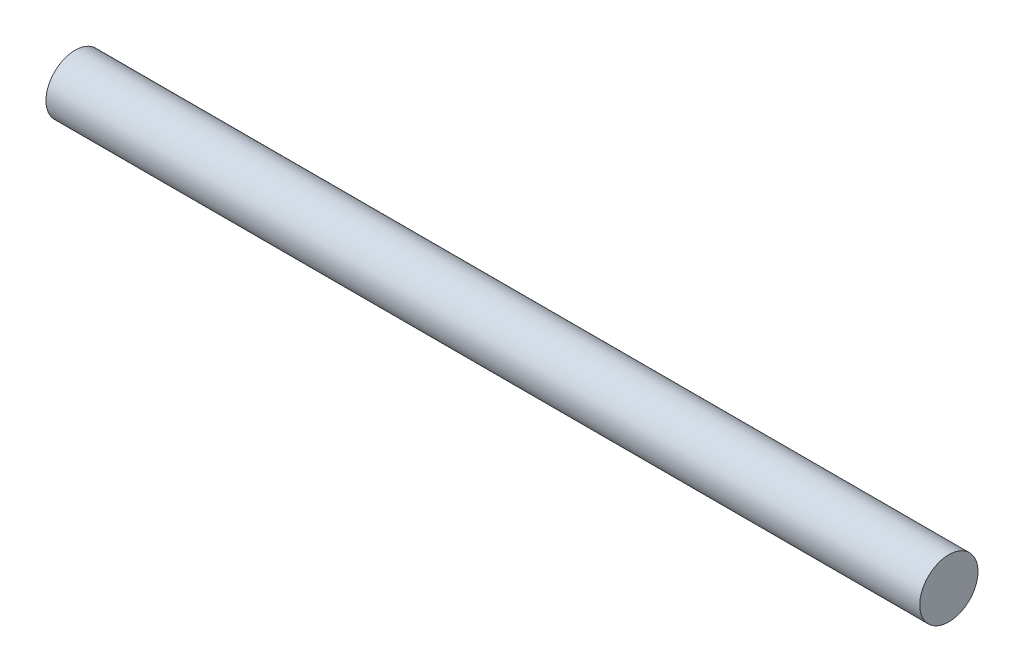
SolidWorks part; units mm, degrees
material "6061 Alloy"
ref_plane "Front Plane" through (0, 0, 0) normal (0, 0, 1) x (1, 0, 0)
ref_plane "Top Plane" through (0, 0, 0) normal (0, 1, 0) x (1, 0, 0)
ref_plane "Right Plane" through (0, 0, 0) normal (1, 0, 0) x (0, 0, -1)
sketch "Sketch2" plane through (0, 0, 0) normal (1, 0, 0) x (0, 0, -1)
  circle A0 centre (0, 0) radius 5
  dimension "D1" = 10
extrude "Boss-Extrude1" add sketch "Sketch2" along normal blind 150
